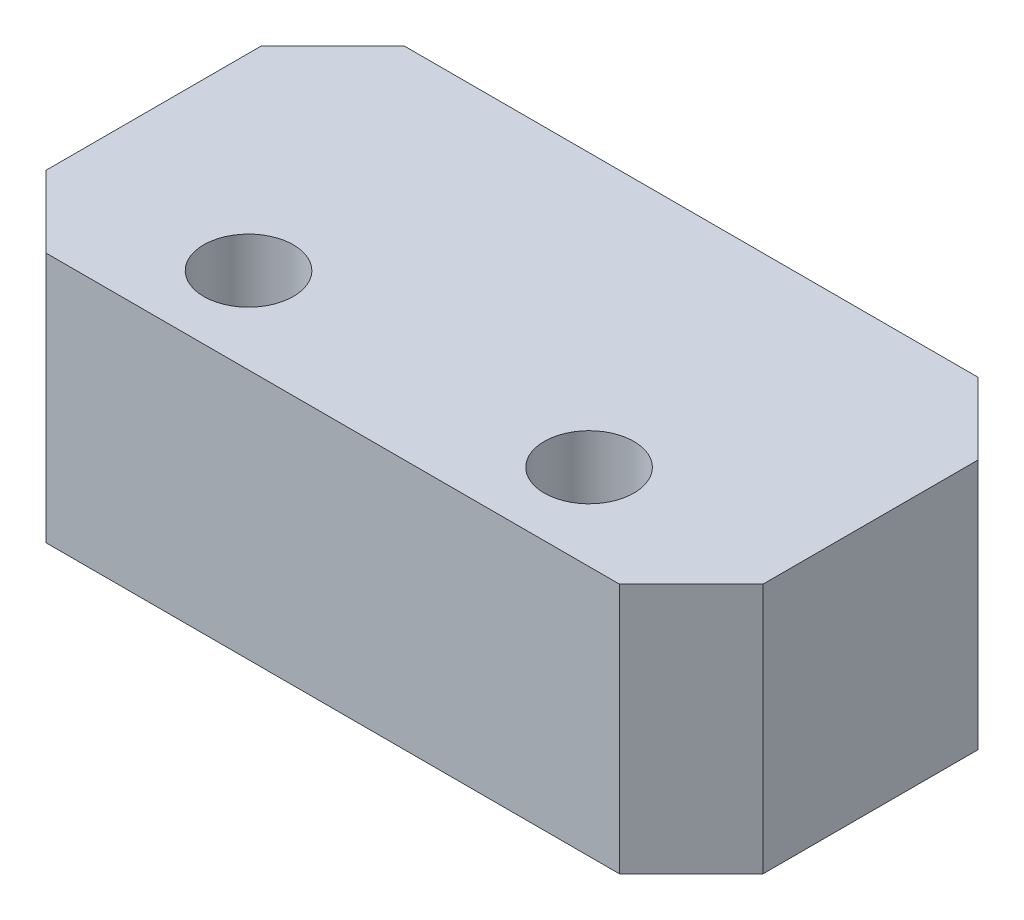
SolidWorks part; units mm, degrees
material "ABS"
ref_plane "Plan de face" through (0, 0, 0) normal (0, 0, 1) x (1, 0, 0)
ref_plane "Plan de dessus" through (0, 0, 0) normal (0, 1, 0) x (1, 0, 0)
ref_plane "Plan de droite" through (0, 0, 0) normal (1, 0, 0) x (0, 0, -1)
sketch "Esquisse1" plane through (0, 0, 0) normal (0, 1, 0) x (1, 0, 0)
  line L0 (0, 0) -> (0, -2.6) construction
  line L1 (-10, -5) -> (10, -5)
  line L2 (-10, -5) -> (-10, 5)
  line L3 (-10, 5) -> (10, 5)
  line L4 (10, -5) -> (10, 5)
  line L5 (-10, -5) -> (10, 5) construction
  line L6 (-10, 5) -> (10, -5) construction
  line L7 (-4.75, -2.6) -> (4.75, -2.6) construction
  circle A0 centre (4.75, -2.6) radius 1.25
  circle A1 centre (-4.75, -2.6) radius 1.25
  point P0 (0, 0)
  dimension "D5" = 2.5
  dimension "D6" = 2.5
  dimension "D1" = 20
  dimension "D2" = 10
  dimension "D3" = 9.5
  dimension "D4" = 7.6
extrude "Boss.-Extru.1" add sketch "Esquisse1" along normal blind 7
chamfer "Chanfrein1" distance 2 angle 45 4 edges at (-10, 3.5, -5) (-10, 3.5, 5) (10, 3.5, -5) (10, 3.5, 5)
